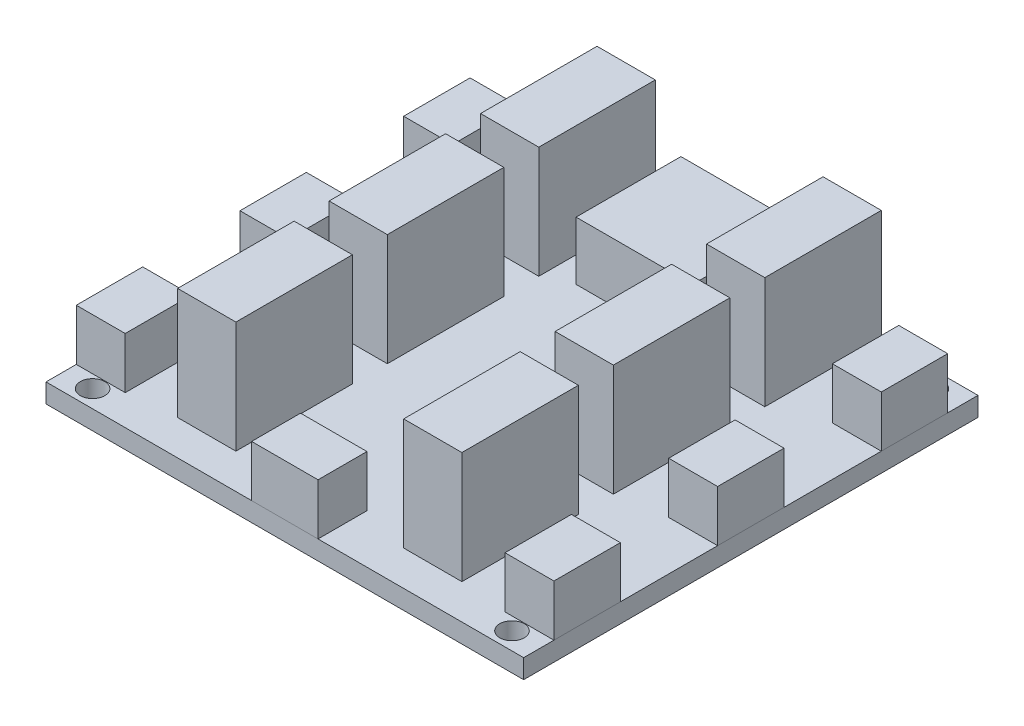
SolidWorks part; units mm, degrees
ref_plane "前视基准面" through (0, 0, 0) normal (0, 0, 1) x (1, 0, 0)
ref_plane "上视基准面" through (0, 0, 0) normal (0, 1, 0) x (1, 0, 0)
ref_plane "右视基准面" through (0, 0, 0) normal (1, 0, 0) x (0, 0, -1)
sketch "草图1" plane through (0, 0, 0) normal (0, 1, 0) x (1, 0, 0)
  line L1 (-20.5, -19.5) -> (20.5, -19.5)
  line L2 (-20.5, -19.5) -> (-20.5, 19.5)
  line L3 (-20.5, 19.5) -> (20.5, 19.5)
  line L4 (20.5, -19.5) -> (20.5, 19.5)
  line L5 (0, 19.5) -> (0, -19.5) construction
  line L6 (-20.5, 0) -> (20.5, 0) construction
  line L7 (-18, -18) -> (18, -18) construction
  line L8 (-18, -18) -> (-18, 18) construction
  line L9 (-18, 18) -> (18, 18) construction
  line L10 (18, -18) -> (18, 18) construction
  line L11 (0, 18) -> (0, -18) construction
  line L12 (-18, 0) -> (18, 0) construction
  circle A0 centre (18, 18) radius 1.05
  circle A1 centre (-18, 18) radius 1.05
  circle A2 centre (-18, -18) radius 1.05
  circle A3 centre (18, -18) radius 1.05
  point P0 (0, 0)
  point P4 (0, 0)
  dimension "D5" = 2.1
  dimension "D1" = 39
  dimension "D2" = 41
  dimension "D3" = 36
  dimension "D4" = 36
extrude "板厚" add sketch "草图1" along normal blind 1.64
sketch "草图3" plane through (0, 1.64, 0) normal (0, 1, 0) x (1, 0, 0)
  line L0 (20.5, 19.5) -> (-20.5, 19.5) construction
  line L1 (-5, 10.5) -> (5, 10.5)
  line L2 (-5, 10.5) -> (-5, 19.5)
  line L3 (-5, 19.5) -> (5, 19.5)
  line L4 (5, 10.5) -> (5, 19.5)
  line L5 (0, 19.5) -> (0, 10.5) construction
  line L6 (-5, 15) -> (5, 15) construction
  point P0 (0, 15)
  dimension "D1" = 10
  dimension "D2" = 9
extrude "侧向xt30" add sketch "草图3" along normal blind 5 separate body
sketch "草图4" plane through (0, 1.64, 0) normal (0, 1, 0) x (1, 0, 0)
  line L0 (20.5, -19.5) -> (20.5, 19.5) construction
  line L1 (16.3, 16.9) -> (20.5, 16.9)
  line L2 (16.3, 16.9) -> (16.3, 11.2)
  line L3 (16.3, 11.2) -> (20.5, 11.2)
  line L4 (20.5, 16.9) -> (20.5, 11.2)
  line L5 (0, 0) -> (20.5, 0) construction
  line L6 (20.5, 19.5) -> (-20.5, 19.5) construction
  line L7 (16.3, 2.85) -> (20.5, 2.85)
  line L8 (16.3, 2.85) -> (16.3, -2.85)
  line L9 (16.3, -2.85) -> (20.5, -2.85)
  line L10 (20.5, 2.85) -> (20.5, -2.85)
  line L11 (16.3, -11.2) -> (20.5, -11.2)
  line L12 (20.5, -16.9) -> (20.5, -11.2)
  line L13 (16.3, -16.9) -> (20.5, -16.9)
  line L14 (16.3, -16.9) -> (16.3, -11.2)
  line L15 (0, 0) -> (0, 24.689) construction
  line L16 (-16.3, -16.9) -> (-16.3, -11.2)
  line L17 (-16.3, -16.9) -> (-20.5, -16.9)
  line L18 (-20.5, -16.9) -> (-20.5, -11.2)
  line L19 (-16.3, -11.2) -> (-20.5, -11.2)
  line L20 (-16.3, -2.85) -> (-20.5, -2.85)
  line L21 (-20.5, 2.85) -> (-20.5, -2.85)
  line L22 (-16.3, 2.85) -> (-20.5, 2.85)
  line L23 (-16.3, 2.85) -> (-16.3, -2.85)
  line L24 (-16.3, 11.2) -> (-20.5, 11.2)
  line L25 (-20.5, 16.9) -> (-20.5, 11.2)
  line L26 (-16.3, 16.9) -> (-20.5, 16.9)
  line L27 (-16.3, 16.9) -> (-16.3, 11.2)
  line L28 (-20.5, -19.5) -> (20.5, -19.5) construction
  line L29 (-2.85, -19.5) -> (2.85, -19.5)
  line L30 (-2.85, -19.5) -> (-2.85, -15.3)
  line L31 (-2.85, -15.3) -> (2.85, -15.3)
  line L32 (2.85, -19.5) -> (2.85, -15.3)
  line L33 (0, 0) -> (0, -19.5) construction
  dimension "D1" = 5.7
  dimension "D2" = 4.2
  dimension "D3" = 2.6
extrude "侧向can " add sketch "草图4" along normal blind 4.4 separate body
sketch "草图5" plane through (0, 1.64, 0) normal (0, 1, 0) x (1, 0, 0)
  line L0 (20.5, 19.5) -> (-20.5, 19.5) construction
  line L1 (-12.2, 19.5) -> (-7.2, 19.5)
  line L2 (-12.2, 19.5) -> (-12.2, 9.5)
  line L3 (-12.2, 9.5) -> (-7.2, 9.5)
  line L4 (-7.2, 19.5) -> (-7.2, 9.5)
  line L5 (-5, 19.5) -> (-5, 10.5) construction
  line L6 (-12.2, 6.5) -> (-12.2, -3.5)
  line L7 (-12.2, 6.5) -> (-7.2, 6.5)
  line L8 (-7.2, 6.5) -> (-7.2, -3.5)
  line L9 (-12.2, -3.5) -> (-7.2, -3.5)
  line L10 (-12.2, -6.5) -> (-12.2, -16.5)
  line L11 (-12.2, -6.5) -> (-7.2, -6.5)
  line L12 (-7.2, -6.5) -> (-7.2, -16.5)
  line L13 (-12.2, -16.5) -> (-7.2, -16.5)
  line L14 (0, 0) -> (0, -12.3369) construction
  line L15 (12.2, -16.5) -> (7.2, -16.5)
  line L16 (7.2, -6.5) -> (7.2, -16.5)
  line L17 (12.2, -6.5) -> (7.2, -6.5)
  line L18 (12.2, -6.5) -> (12.2, -16.5)
  line L19 (12.2, -3.5) -> (7.2, -3.5)
  line L20 (7.2, 6.5) -> (7.2, -3.5)
  line L21 (12.2, 6.5) -> (7.2, 6.5)
  line L22 (12.2, 6.5) -> (12.2, -3.5)
  line L23 (7.2, 19.5) -> (7.2, 9.5)
  line L24 (12.2, 9.5) -> (7.2, 9.5)
  line L25 (12.2, 19.5) -> (12.2, 9.5)
  line L26 (12.2, 19.5) -> (7.2, 19.5)
  dimension "D1" = 5
  dimension "D2" = 10
  dimension "D3" = 2.2
  dimension "D5" = 3
  dimension "D4" = 3
extrude "法向xt30" add sketch "草图5" along normal blind 9.6 separate body
